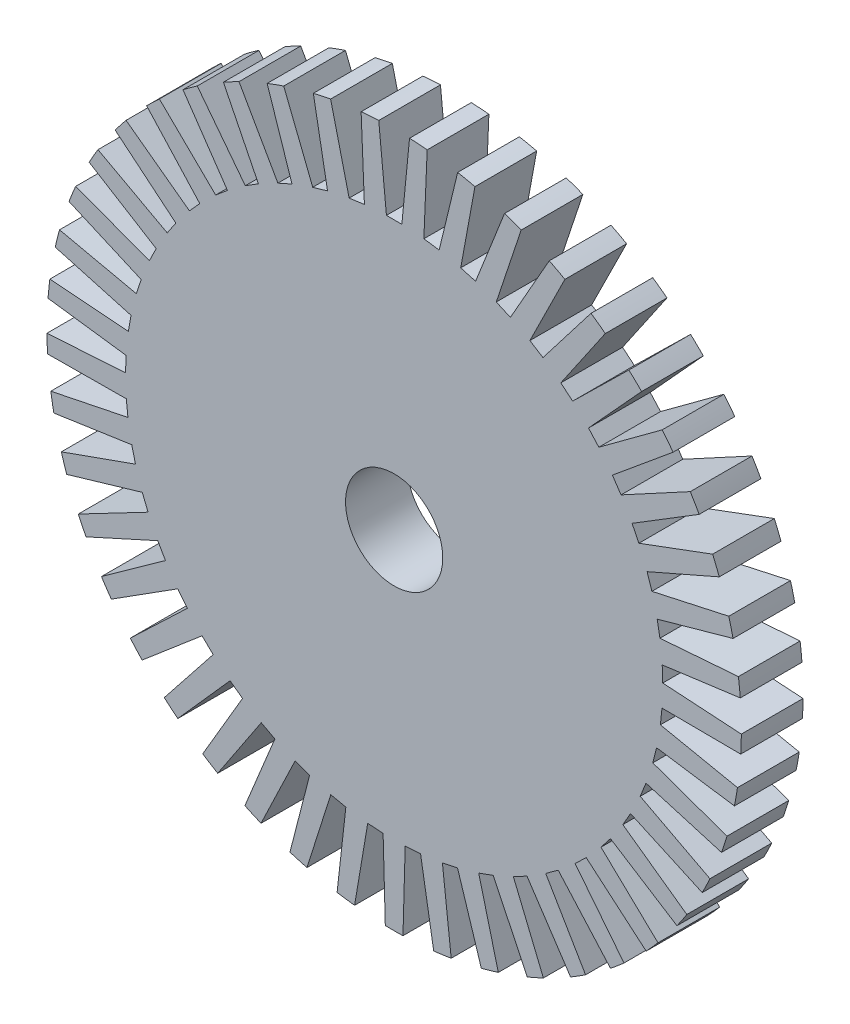
SolidWorks part; units mm, degrees
ref_plane "Front Plane" through (0, 0, 0) normal (0, 0, 1) x (1, 0, 0)
ref_plane "Top Plane" through (0, 0, 0) normal (0, 1, 0) x (1, 0, 0)
ref_plane "Right Plane" through (0, 0, 0) normal (1, 0, 0) x (0, 0, -1)
sketch "Sketch1" plane through (0, 0, 0) normal (0, 0, 1) x (1, 0, 0)
  line L0 (0, 23.8979) -> (0, 11.29) construction
  line L1 (-1, 22.5) -> (1, 22.5)
  line L2 (-0.5, 17.4001) -> (0.5, 17.4001)
  line L3 (1, 22.5) -> (0.5, 17.4001)
  line L4 (-1, 22.5) -> (-0.5, 17.4001)
  line L5 (2.1411, 22.4202) -> (1.9265, 17.3003)
  line L6 (4.1217, 22.1419) -> (2.9168, 17.1612)
  line L7 (1.9265, 17.3003) -> (2.9168, 17.1612)
  line L8 (2.1411, 22.4202) -> (4.1217, 22.1419)
  line L9 (5.2406, 21.904) -> (4.3155, 16.8639)
  line L10 (7.1631, 21.3528) -> (5.2767, 16.5882)
  line L11 (4.3155, 16.8639) -> (5.2767, 16.5882)
  line L12 (5.2406, 21.904) -> (7.1631, 21.3528)
  line L13 (8.238, 20.9615) -> (6.6205, 16.0991)
  line L14 (10.0651, 20.148) -> (7.534, 15.6924)
  line L15 (6.6205, 16.0991) -> (7.534, 15.6924)
  line L16 (8.238, 20.9615) -> (10.0651, 20.148)
  line L17 (11.0751, 19.611) -> (8.7966, 15.0211)
  line L18 (12.7712, 18.5512) -> (9.6447, 14.4912)
  line L19 (8.7966, 15.0211) -> (9.6447, 14.4912)
  line L20 (11.0751, 19.611) -> (12.7712, 18.5512)
  line L21 (13.6967, 17.8788) -> (10.8015, 13.6506)
  line L22 (15.2288, 16.5932) -> (11.5676, 13.0079)
  line L23 (10.8015, 13.6506) -> (11.5676, 13.0079)
  line L24 (13.6967, 17.8788) -> (15.2288, 16.5932)
  line L25 (16.0516, 15.7986) -> (12.5962, 12.0145)
  line L26 (17.3899, 14.3123) -> (13.2654, 11.2714)
  line L27 (12.5962, 12.0145) -> (13.2654, 11.2714)
  line L28 (16.0516, 15.7986) -> (17.3899, 14.3123)
  line L29 (18.0942, 13.4109) -> (14.1457, 10.1445)
  line L30 (19.2125, 11.7528) -> (14.7049, 9.3155)
  line L31 (14.1457, 10.1445) -> (14.7049, 9.3155)
  line L32 (18.0942, 13.4109) -> (19.2125, 11.7528)
  line L33 (19.7845, 10.7621) -> (15.4199, 8.0771)
  line L34 (20.6612, 8.9646) -> (15.8583, 7.1783)
  line L35 (15.4199, 8.0771) -> (15.8583, 7.1783)
  line L36 (19.7845, 10.7621) -> (20.6612, 8.9646)
  line L37 (21.0898, 7.9039) -> (16.394, 5.8525)
  line L38 (21.7078, 6.0018) -> (16.703, 4.9014)
  line L39 (16.394, 5.8525) -> (16.703, 4.9014)
  line L40 (21.0898, 7.9039) -> (21.7078, 6.0018)
  line L41 (21.9845, 4.8919) -> (17.0489, 3.5139)
  line L42 (22.3318, 2.9223) -> (17.2226, 2.5291)
  line L43 (17.0489, 3.5139) -> (17.2226, 2.5291)
  line L44 (21.9845, 4.8919) -> (22.3318, 2.9223)
  line L45 (22.4514, 1.7846) -> (17.372, 1.1069)
  line L46 (22.5212, -0.2142) -> (17.4069, 0.1076)
  line L47 (17.372, 1.1069) -> (17.4069, 0.1076)
  line L48 (22.4514, 1.7846) -> (22.5212, -0.2142)
  line L49 (22.4813, -1.3574) -> (17.357, -1.3215)
  line L50 (22.2722, -3.3464) -> (17.2525, -2.3161)
  line L51 (17.357, -1.3215) -> (17.2525, -2.3161)
  line L52 (22.4813, -1.3574) -> (22.2722, -3.3464)
  line L53 (22.0736, -4.4729) -> (17.0042, -3.7243)
  line L54 (21.5897, -6.4135) -> (16.7623, -4.6946)
  line L55 (17.0042, -3.7243) -> (16.7623, -4.6946)
  line L56 (22.0736, -4.4729) -> (21.5897, -6.4135)
  line L57 (21.2362, -7.5015) -> (16.3204, -6.0546)
  line L58 (20.487, -9.3558) -> (15.9458, -6.9818)
  line L59 (16.3204, -6.0546) -> (15.9458, -6.9818)
  line L60 (21.2362, -7.5015) -> (20.487, -9.3558)
  line L61 (19.9856, -10.384) -> (15.3189, -8.267)
  line L62 (18.9856, -12.116) -> (14.8189, -9.1331)
  line L63 (15.3189, -8.267) -> (14.8189, -9.1331)
  line L64 (19.9856, -10.384) -> (18.9856, -12.116)
  line L65 (18.3459, -13.0644) -> (14.0193, -10.3186)
  line L66 (17.1146, -14.6404) -> (13.4036, -11.1066)
  line L67 (14.0193, -10.3186) -> (13.4036, -11.1066)
  line L68 (18.3459, -13.0644) -> (17.1146, -14.6404)
  line L69 (16.3492, -15.4905) -> (12.4468, -12.1693)
  line L70 (14.9105, -16.8798) -> (11.7275, -12.8639)
  line L71 (12.4468, -12.1693) -> (11.7275, -12.8639)
  line L72 (16.3492, -15.4905) -> (14.9105, -16.8798)
  line L73 (14.0342, -17.6151) -> (10.632, -13.7831)
  line L74 (12.4162, -18.7907) -> (9.823, -14.3709)
  line L75 (10.632, -13.7831) -> (9.823, -14.3709)
  line L76 (14.0342, -17.6151) -> (12.4162, -18.7907)
  line L77 (11.4461, -19.3968) -> (8.6103, -15.1286)
  line L78 (9.6802, -20.3358) -> (7.7274, -15.5981)
  line L79 (8.6103, -15.1286) -> (7.7274, -15.5981)
  line L80 (11.4461, -19.3968) -> (9.6802, -20.3358)
  line L81 (8.6351, -20.8011) -> (6.421, -16.1797)
  line L82 (6.7558, -21.4851) -> (5.4813, -16.5217)
  line L83 (6.421, -16.1797) -> (5.4813, -16.5217)
  line L84 (8.6351, -20.8011) -> (6.7558, -21.4851)
  line L85 (5.6562, -21.8004) -> (4.1068, -16.9159)
  line L86 (3.6999, -22.2162) -> (3.1286, -17.1238)
  line L87 (4.1068, -16.9159) -> (3.1286, -17.1238)
  line L88 (5.6562, -21.8004) -> (3.6999, -22.2162)
  line L89 (2.5671, -22.3754) -> (1.7126, -17.3228)
  line L90 (0.572, -22.5149) -> (0.715, -17.3926)
  line L91 (1.7126, -17.3228) -> (0.715, -17.3926)
  line L92 (2.5671, -22.3754) -> (0.572, -22.5149)
  line L93 (-0.572, -22.5149) -> (-0.715, -17.3926)
  line L94 (-2.5671, -22.3754) -> (-1.7126, -17.3228)
  line L95 (-0.715, -17.3926) -> (-1.7126, -17.3228)
  line L96 (-0.572, -22.5149) -> (-2.5671, -22.3754)
  line L97 (-3.6999, -22.2162) -> (-3.1286, -17.1238)
  line L98 (-5.6562, -21.8004) -> (-4.1068, -16.9159)
  line L99 (-3.1286, -17.1238) -> (-4.1068, -16.9159)
  line L100 (-3.6999, -22.2162) -> (-5.6562, -21.8004)
  line L101 (-6.7558, -21.4851) -> (-5.4813, -16.5217)
  line L102 (-8.6351, -20.8011) -> (-6.421, -16.1797)
  line L103 (-5.4813, -16.5217) -> (-6.421, -16.1797)
  line L104 (-6.7558, -21.4851) -> (-8.6351, -20.8011)
  line L105 (-9.6802, -20.3358) -> (-7.7274, -15.5981)
  line L106 (-11.4461, -19.3968) -> (-8.6103, -15.1286)
  line L107 (-7.7274, -15.5981) -> (-8.6103, -15.1286)
  line L108 (-9.6802, -20.3358) -> (-11.4461, -19.3968)
  line L109 (-12.4162, -18.7907) -> (-9.823, -14.3709)
  line L110 (-14.0342, -17.6151) -> (-10.632, -13.7831)
  line L111 (-9.823, -14.3709) -> (-10.632, -13.7831)
  line L112 (-12.4162, -18.7907) -> (-14.0342, -17.6151)
  line L113 (-14.9105, -16.8798) -> (-11.7275, -12.8639)
  line L114 (-16.3492, -15.4905) -> (-12.4468, -12.1693)
  line L115 (-11.7275, -12.8639) -> (-12.4468, -12.1693)
  line L116 (-14.9105, -16.8798) -> (-16.3492, -15.4905)
  line L117 (-17.1146, -14.6404) -> (-13.4036, -11.1066)
  line L118 (-18.3459, -13.0644) -> (-14.0193, -10.3186)
  line L119 (-13.4036, -11.1066) -> (-14.0193, -10.3186)
  line L120 (-17.1146, -14.6404) -> (-18.3459, -13.0644)
  line L121 (-18.9856, -12.116) -> (-14.8189, -9.1331)
  line L122 (-19.9856, -10.384) -> (-15.3189, -8.267)
  line L123 (-14.8189, -9.1331) -> (-15.3189, -8.267)
  line L124 (-18.9856, -12.116) -> (-19.9856, -10.384)
  line L125 (-20.487, -9.3558) -> (-15.9458, -6.9818)
  line L126 (-21.2362, -7.5015) -> (-16.3204, -6.0546)
  line L127 (-15.9458, -6.9818) -> (-16.3204, -6.0546)
  line L128 (-20.487, -9.3558) -> (-21.2362, -7.5015)
  line L129 (-21.5897, -6.4135) -> (-16.7623, -4.6946)
  line L130 (-22.0736, -4.4729) -> (-17.0042, -3.7243)
  line L131 (-16.7623, -4.6946) -> (-17.0042, -3.7243)
  line L132 (-21.5897, -6.4135) -> (-22.0736, -4.4729)
  line L133 (-22.2722, -3.3464) -> (-17.2525, -2.3161)
  line L134 (-22.4813, -1.3574) -> (-17.357, -1.3215)
  line L135 (-17.2525, -2.3161) -> (-17.357, -1.3215)
  line L136 (-22.2722, -3.3464) -> (-22.4813, -1.3574)
  line L137 (-22.5212, -0.2142) -> (-17.4069, 0.1076)
  line L138 (-22.4514, 1.7846) -> (-17.372, 1.1069)
  line L139 (-17.4069, 0.1076) -> (-17.372, 1.1069)
  line L140 (-22.5212, -0.2142) -> (-22.4514, 1.7846)
  line L141 (-22.3318, 2.9223) -> (-17.2226, 2.5291)
  line L142 (-21.9845, 4.8919) -> (-17.0489, 3.5139)
  line L143 (-17.2226, 2.5291) -> (-17.0489, 3.5139)
  line L144 (-22.3318, 2.9223) -> (-21.9845, 4.8919)
  line L145 (-21.7078, 6.0018) -> (-16.703, 4.9014)
  line L146 (-21.0898, 7.9039) -> (-16.394, 5.8525)
  line L147 (-16.703, 4.9014) -> (-16.394, 5.8525)
  line L148 (-21.7078, 6.0018) -> (-21.0898, 7.9039)
  line L149 (-20.6612, 8.9646) -> (-15.8583, 7.1783)
  line L150 (-19.7845, 10.7621) -> (-15.4199, 8.0771)
  line L151 (-15.8583, 7.1783) -> (-15.4199, 8.0771)
  line L152 (-20.6612, 8.9646) -> (-19.7845, 10.7621)
  line L153 (-19.2125, 11.7528) -> (-14.7049, 9.3155)
  line L154 (-18.0942, 13.4109) -> (-14.1457, 10.1445)
  line L155 (-14.7049, 9.3155) -> (-14.1457, 10.1445)
  line L156 (-19.2125, 11.7528) -> (-18.0942, 13.4109)
  line L157 (-17.3899, 14.3123) -> (-13.2654, 11.2714)
  line L158 (-16.0516, 15.7986) -> (-12.5962, 12.0145)
  line L159 (-13.2654, 11.2714) -> (-12.5962, 12.0145)
  line L160 (-17.3899, 14.3123) -> (-16.0516, 15.7986)
  line L161 (-15.2288, 16.5932) -> (-11.5676, 13.0079)
  line L162 (-13.6967, 17.8788) -> (-10.8015, 13.6506)
  line L163 (-11.5676, 13.0079) -> (-10.8015, 13.6506)
  line L164 (-15.2288, 16.5932) -> (-13.6967, 17.8788)
  line L165 (-12.7712, 18.5512) -> (-9.6447, 14.4912)
  line L166 (-11.0751, 19.611) -> (-8.7966, 15.0211)
  line L167 (-9.6447, 14.4912) -> (-8.7966, 15.0211)
  line L168 (-12.7712, 18.5512) -> (-11.0751, 19.611)
  line L169 (-10.0651, 20.148) -> (-7.534, 15.6924)
  line L170 (-8.238, 20.9615) -> (-6.6205, 16.0991)
  line L171 (-7.534, 15.6924) -> (-6.6205, 16.0991)
  line L172 (-10.0651, 20.148) -> (-8.238, 20.9615)
  line L173 (-7.1631, 21.3528) -> (-5.2767, 16.5882)
  line L174 (-5.2406, 21.904) -> (-4.3155, 16.8639)
  line L175 (-5.2767, 16.5882) -> (-4.3155, 16.8639)
  line L176 (-7.1631, 21.3528) -> (-5.2406, 21.904)
  line L177 (-4.1217, 22.1419) -> (-2.9168, 17.1612)
  line L178 (-2.1411, 22.4202) -> (-1.9265, 17.3003)
  line L179 (-2.9168, 17.1612) -> (-1.9265, 17.3003)
  line L180 (-4.1217, 22.1419) -> (-2.1411, 22.4202)
  circle A0 centre (0, 0) radius 22.5
  circle A1 centre (0, 0) radius 17.4001
  circle A2 centre (0, 0) radius 3.15
  point P11 (0, 17.4001)
  point P12 (0, 22.5)
  point P191 (0, 0)
  dimension "D1" = 45
  dimension "D2" = 34.8002
  dimension "D5" = 6.3
  dimension "D3" = 1
  dimension "D4" = 45
extrude "Boss-Extrude1" add sketch "Sketch1" along normal blind 4
